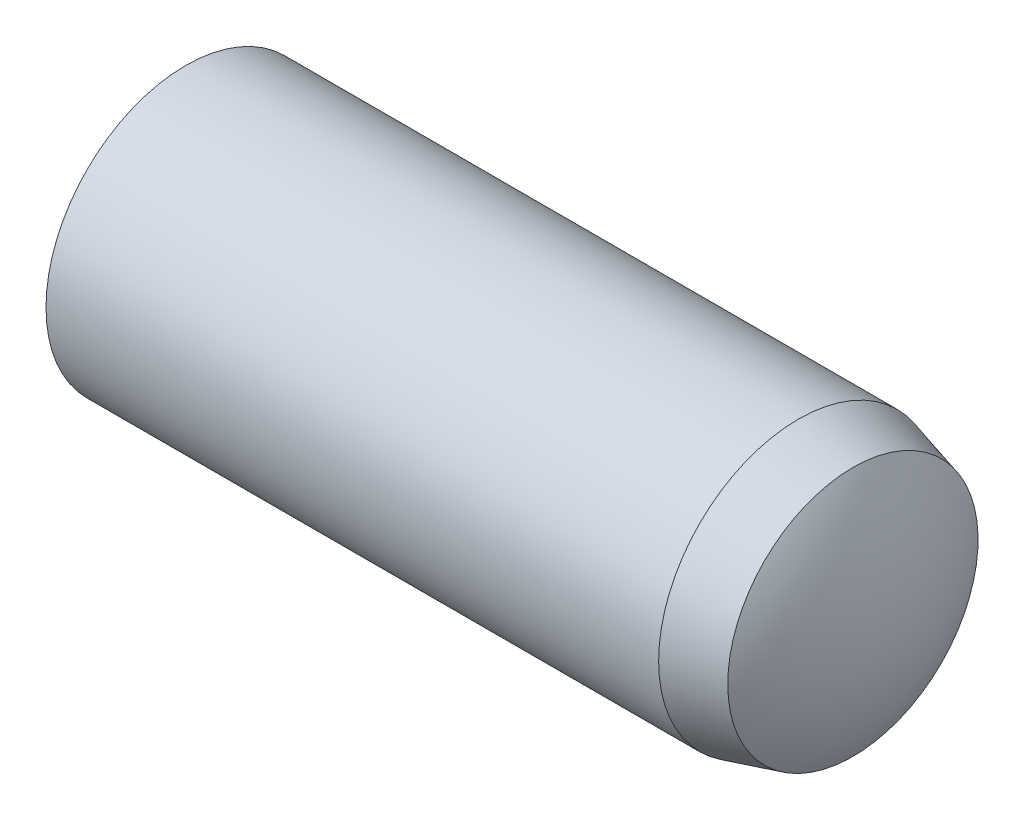
SolidWorks part; units mm, degrees
material "AISI 304"
ref_plane "Front Plane" through (0, 0, 0) normal (0, 0, 1) x (1, 0, 0)
ref_plane "Top Plane" through (0, 0, 0) normal (0, 1, 0) x (1, 0, 0)
ref_plane "Right Plane" through (0, 0, 0) normal (1, 0, 0) x (0, 0, -1)
sketch "Sketch1" plane through (0, 0, 0) normal (0, 0, 1) x (1, 0, 0)
  line L0 (-4, 0) -> (4, 0) construction
  line L1 (4, 1.5) -> (4, -1.5) construction
  line L2 (-4, 1.5) -> (-4, -1.5) construction
  line L3 (3.025, 1.5) -> (3.025, -1.5) construction
  line L4 (-3.55, 1.5) -> (-3.55, -1.5) construction
  line L5 (-4, 0) -> (-3.55, 0) construction
  line L6 (4, 0) -> (3.025, 0) construction
  line L7 (3.61, 1.5) -> (3.61, -1.5) construction
  dimension "Dia" = 3
  dimension "Length" = 8
  dimension "D1" = 0.975
  dimension "D2" = 0.45
  dimension "D3" = 0.585
sketch "Sketch2" plane through (0, 0, 0) normal (1, 0, 0) x (0, 0, -1)
  circle A0 centre (0, 0) radius 1.5
extrude "Extrude1" add sketch "Sketch2" against normal up to vertex (4 mm away) and the other way up to vertex (4 mm away) up to point (-4, 0, 0) other way up to point (4, 0, 0)
sketch "Sketch5" plane through (0, 0, 0) normal (0, 0, 1) x (1, 0, 0)
  line L0 (3.025, 1.5) -> (3.025, 2)
  line L1 (3.025, 2) -> (4.5, 2)
  line L2 (4.5, 2) -> (4.5, 0)
  line L3 (4, 0) -> (4.5, 0)
  line L5 (-3.55, 1.5) -> (-3.55, 2)
  line L6 (-3.55, 2) -> (-4.5, 2)
  line L7 (-4.5, 2) -> (-4.5, 0)
  line L8 (3.025, 1.5) -> (3.61, 1.3432)
  line L10 (-4, 0) -> (-4.5, 0)
  line L11 (-4, 1.5) -> (-4, -1.5) construction
  line L13 (3.025, 1.5) -> (3.025, -1.5) construction
  line L15 (-4, 0) -> (4, 0) construction
  line L16 (3.61, 1.5) -> (3.61, -1.5) construction
  line L17 (4, 1.5) -> (4, -1.5) construction
  arc A0 (3.61, 1.3432) -> (4, 0) centre (1.4918, 0) cw
  arc A1 (-3.55, 1.5) -> (-4, 0) centre (-1.275, 0) ccw
  dimension "D1" = 15
  dimension "D2" = 0.5
revolve "Cut-Revolve1" cut sketch "Sketch5" angle 360 about L0
equation "\"D1@Sketch1\" = \"Dia@Sketch1\"*.325"
equation "\"D2@Sketch1\" = \"Dia@Sketch1\"*.15"
equation "\"D3@Sketch1\" = \"D1@Sketch1\"*.6"
